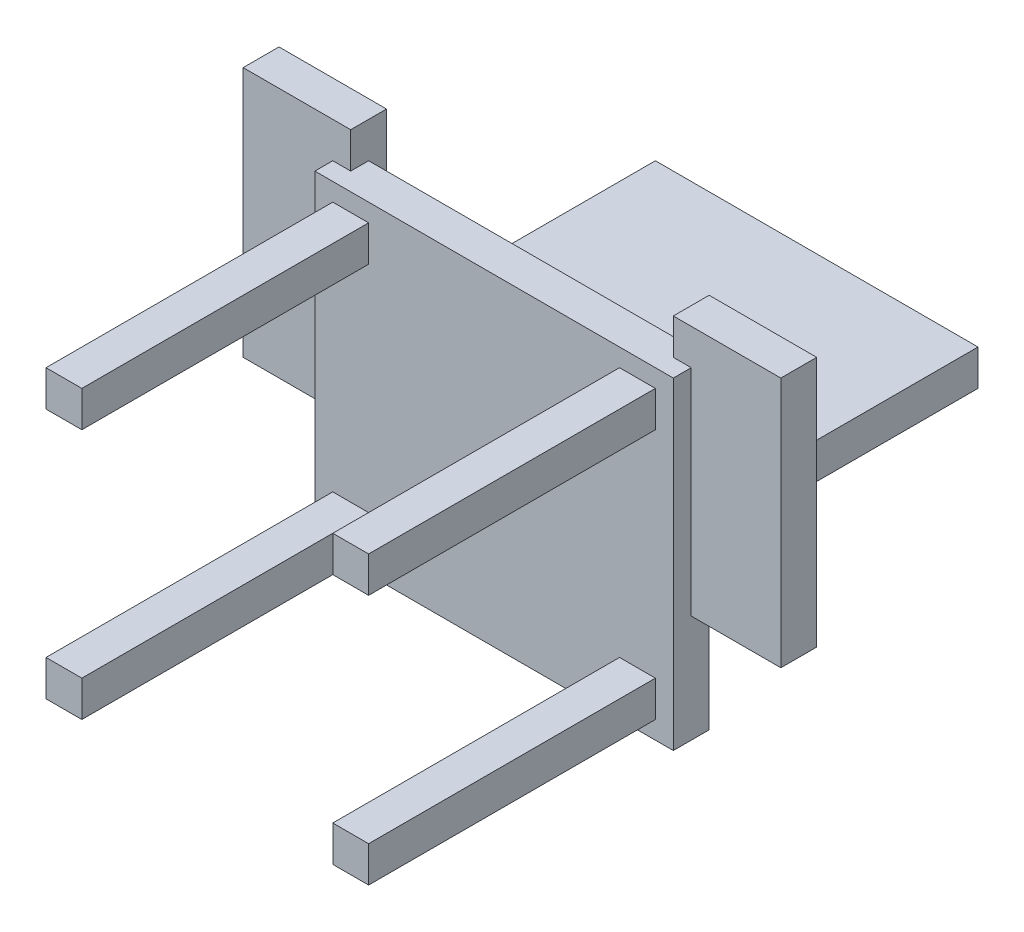
SolidWorks part; units mm, degrees
ref_plane "前视基准面" through (0, 0, 0) normal (0, 0, 1) x (1, 0, 0)
ref_plane "上视基准面" through (0, 0, 0) normal (0, 1, 0) x (1, 0, 0)
ref_plane "右视基准面" through (0, 0, 0) normal (1, 0, 0) x (0, 0, -1)
other "Configuration Table"
sketch "草图1" plane through (0, 0, 0) normal (0, 0, 1) x (1, 0, 0)
  line L1 (-250, -225) -> (250, -225)
  line L2 (-250, -225) -> (-250, 225)
  line L3 (-250, 225) -> (250, 225)
  line L4 (250, -225) -> (250, 225)
  line L5 (-250, -225) -> (250, 225) construction
  line L6 (-250, 225) -> (250, -225) construction
  point P0 (0, 0)
extrude "凸台-拉伸1" add sketch "草图1" along normal blind 50
sketch "草图2" plane through (0, 0, 0) normal (0, 0, 1) x (1, 0, 0)
  line L1 (-225, -200) -> (-175, -200)
  line L2 (-225, -200) -> (-225, -150)
  line L3 (-225, -150) -> (-175, -150)
  line L4 (-175, -200) -> (-175, -150)
  line L5 (-225, -200) -> (-175, -150) construction
  line L6 (-225, -150) -> (-175, -200) construction
  point P0 (-200, -175)
extrude "凸台-拉伸2" add sketch "草图2" along normal blind 450
sketch "草图3" plane through (0, 0, 0) normal (0, 0, 1) x (1, 0, 0)
  line L1 (175, -200) -> (225, -200)
  line L2 (175, -200) -> (175, -150)
  line L3 (175, -150) -> (225, -150)
  line L4 (225, -200) -> (225, -150)
  line L5 (175, -200) -> (225, -150) construction
  line L6 (175, -150) -> (225, -200) construction
  point P0 (200, -175)
extrude "凸台-拉伸3" add sketch "草图3" along normal blind 450
sketch "草图4" plane through (0, 0, 0) normal (0, 0, 1) x (1, 0, 0)
  line L1 (-225, 150) -> (-175, 150)
  line L2 (-225, 150) -> (-225, 200)
  line L3 (-225, 200) -> (-175, 200)
  line L4 (-175, 150) -> (-175, 200)
  line L5 (-225, 150) -> (-175, 200) construction
  line L6 (-225, 200) -> (-175, 150) construction
  point P0 (-200, 175)
extrude "凸台-拉伸4" add sketch "草图4" along normal blind 450
sketch "草图5" plane through (0, 0, 0) normal (0, 0, 1) x (1, 0, 0)
  line L1 (175, 150) -> (225, 150)
  line L2 (175, 150) -> (175, 200)
  line L3 (175, 200) -> (225, 200)
  line L4 (225, 150) -> (225, 200)
  line L5 (175, 150) -> (225, 200) construction
  line L6 (175, 200) -> (225, 150) construction
  point P0 (200, 175)
extrude "凸台-拉伸5" add sketch "草图5" along normal blind 450
sketch "草图6" plane through (0, 0, 0) normal (0, 0, -1) x (-1, 0, 0)
  line L1 (-225, -25) -> (225, -25)
  line L2 (-225, -25) -> (-225, 25)
  line L3 (-225, 25) -> (225, 25)
  line L4 (225, -25) -> (225, 25)
  line L5 (-225, -25) -> (225, 25) construction
  line L6 (-225, 25) -> (225, -25) construction
  point P0 (0, 0)
extrude "凸台-拉伸6" add sketch "草图6" along normal blind 400
sketch "草图7" plane through (-225, 0, 0) normal (-1, 0, 0) x (0, 0, 1)
  line L0 (0, 225) -> (0, -225) construction
  line L1 (-25, -75) -> (25, -75)
  line L2 (-25, -75) -> (-25, 275)
  line L3 (-25, 275) -> (25, 275)
  line L4 (25, -75) -> (25, 275)
  line L5 (-25, -75) -> (25, 275) construction
  line L6 (-25, 275) -> (25, -75) construction
  point P0 (0, 100)
extrude "凸台-拉伸7" add sketch "草图7" along normal blind 150
sketch "草图8" plane through (225, 0, 0) normal (1, 0, 0) x (0, 0, -1)
  line L0 (0, -225) -> (0, 225) construction
  line L1 (-25, -75) -> (25, -75)
  line L2 (-25, -75) -> (-25, 275)
  line L3 (-25, 275) -> (25, 275)
  line L4 (25, -75) -> (25, 275)
  line L5 (-25, -75) -> (25, 275) construction
  line L6 (-25, 275) -> (25, -75) construction
  point P0 (0, 100)
extrude "凸台-拉伸8" add sketch "草图8" along normal blind 150
